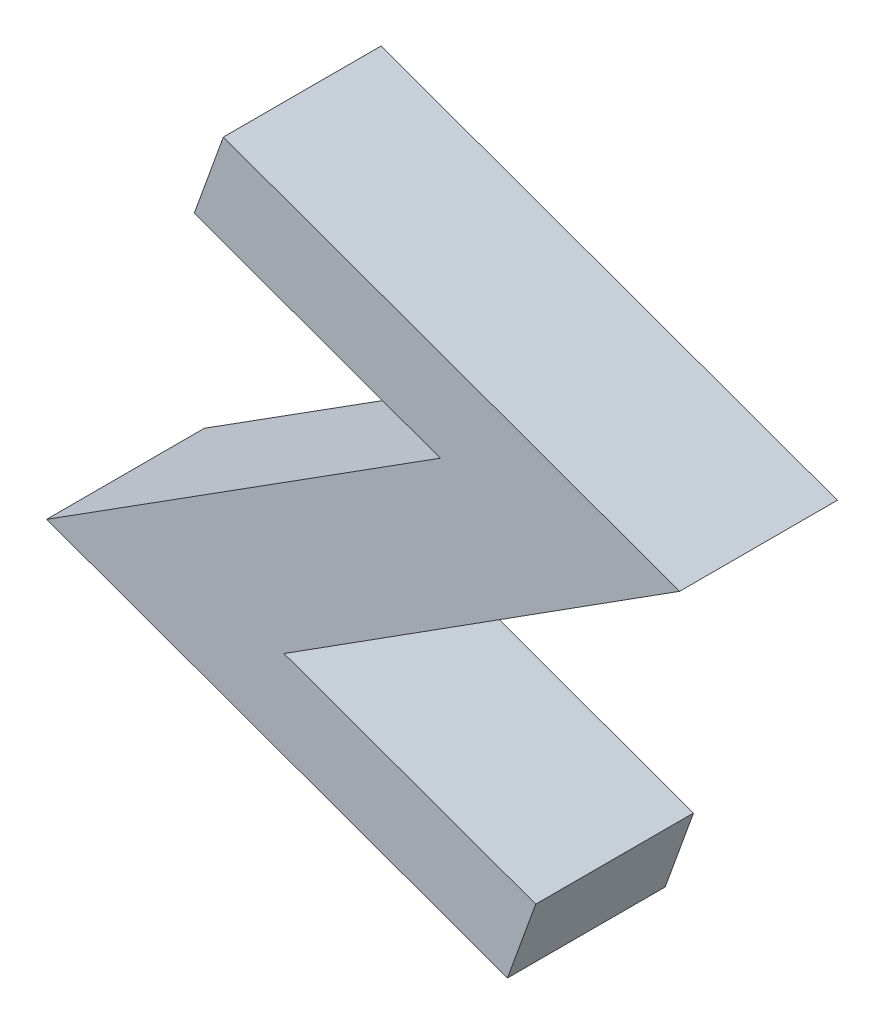
SolidWorks part; units mm, degrees
ref_plane "Front Plane" through (0, 0, 0) normal (0, 0, 1) x (1, 0, 0)
ref_plane "Top Plane" through (0, 0, 0) normal (0, 1, 0) x (1, 0, 0)
ref_plane "Right Plane" through (0, 0, 0) normal (1, 0, 0) x (0, 0, -1)
sketch "Sketch1" plane through (0, 0, 0) normal (0, 0, 1) x (1, 0, 0)
  text T0 "<b><r-20>Z</r></b>" font "Century Gothic" height 19.05
extrude "Boss-Extrude1" add sketch "Sketch1" along normal blind 6.604
